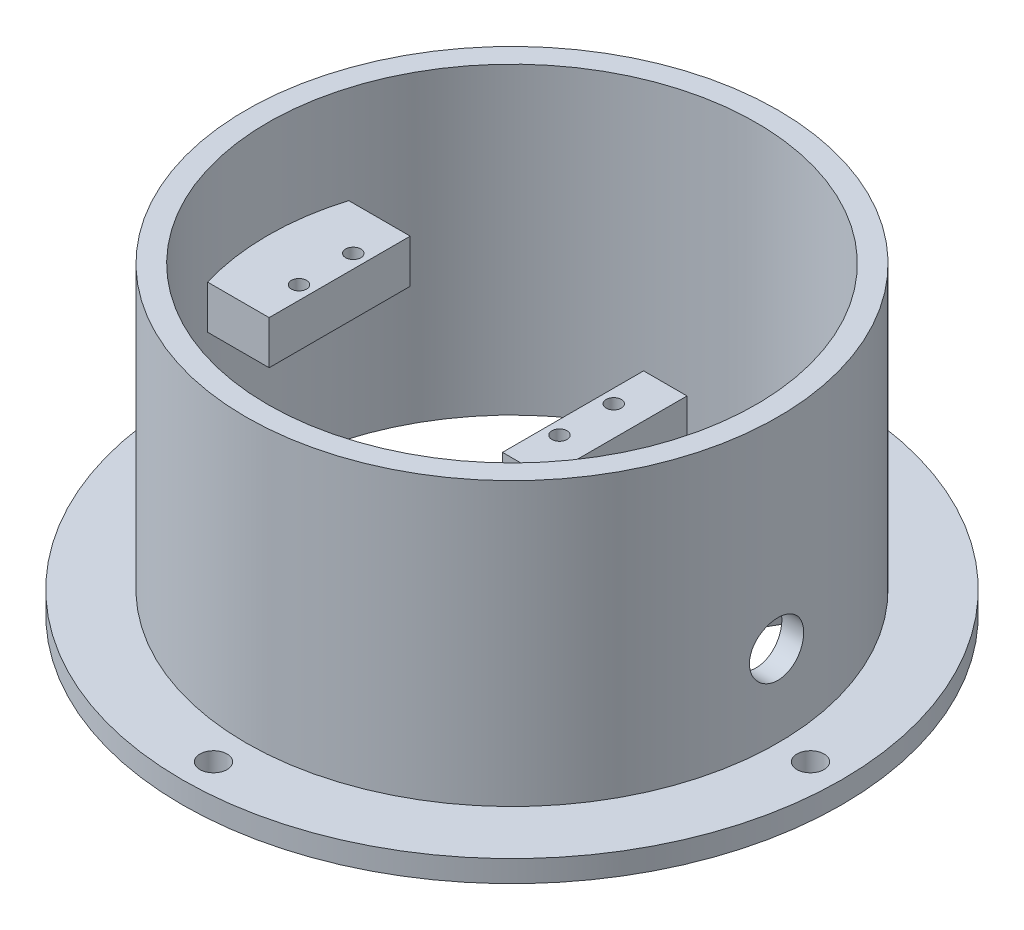
SolidWorks part; units mm, degrees
ref_plane "Front Plane" through (0, 0, 0) normal (0, 0, 1) x (1, 0, 0)
ref_plane "Top Plane" through (0, 0, 0) normal (0, 1, 0) x (1, 0, 0)
ref_plane "Right Plane" through (0, 0, 0) normal (1, 0, 0) x (0, 0, -1)
sketch "Sketch1" plane through (0, 0, 0) normal (0, 1, 0) x (1, 0, 0)
  circle A0 centre (0, 0) radius 45
  circle A1 centre (0, 0) radius 60.75
  dimension "D1" = 90
  dimension "D2" = 121.5
extrude "Boss-Extrude1" add sketch "Sketch1" along normal blind 4
sketch "Sketch2" plane through (0, 4, 0) normal (0, 1, 0) x (1, 0, 0)
  circle A2 centre (0, 0) radius 49
  circle A3 centre (0, 0) radius 49
  circle A5 centre (0, 0) radius 45
  circle A6 centre (0, 0) radius 45
  dimension "D1" = 4
  dimension "D2" = 0
extrude "Boss-Extrude2" add sketch "Sketch2" along normal blind 52
sketch "Sketch3" plane through (0, 0, 0) normal (0, 0, 1) x (1, 0, 0)
  line L0 (0, 0) -> (0, 56) construction
  line L1 (49, 56) -> (-49, 56) construction
  line L2 (-60.75, 0) -> (60.75, 0) construction
  line L3 (11.25, 0) -> (19.25, 0)
  line L4 (11.25, 0) -> (11.25, 38)
  line L5 (11.25, 38) -> (19.25, 38)
  line L6 (19.25, 0) -> (19.25, 38)
  line L7 (45, 56) -> (-45, 56) construction
  line L9 (-46.75, 38) -> (-31.75, 38)
  line L10 (-46.75, 38) -> (-46.75, 30)
  line L11 (-46.75, 30) -> (-31.75, 30)
  line L12 (-31.75, 38) -> (-31.75, 30)
  dimension "D1" = 8
  dimension "D2" = 11.25
  dimension "D3" = 18
  dimension "D4" = 18
  dimension "D5" = 8
  dimension "D6" = 46.75
  dimension "D7" = 15
extrude "Boss-Extrude3" add sketch "Sketch3" along normal mid plane 26
sketch "Sketch4" plane through (11.25, 0, 0) normal (-1, 0, 0) x (0, 0, 1)
  line L0 (0, 0) -> (0, 38) construction
  line L1 (13, 0) -> (-13, 0) construction
  line L2 (13, 38) -> (-13, 38) construction
  line L4 (-5, 5) -> (5, 5)
  line L5 (-5, 5) -> (-5, 28)
  line L6 (-5, 28) -> (5, 28)
  line L7 (5, 5) -> (5, 28)
  line L8 (-5, 5) -> (5, 28) construction
  line L9 (-5, 28) -> (5, 5) construction
  point P6 (0, 16.5)
  dimension "D1" = 5
  dimension "D2" = 10
  dimension "D3" = 10
extrude "Cut-Extrude1" cut sketch "Sketch4" against normal up to surface (8 mm away) up to face at (19.25, 19, 0)
sketch "Sketch5" plane through (11.25, 0, 0) normal (-1, 0, 0) x (0, 0, 1)
  line L0 (0, 28) -> (0, 5) construction
  line L1 (5, 28) -> (-5, 28) construction
  line L2 (-5, 5) -> (5, 5) construction
  circle A0 centre (0, 19) radius 5
  dimension "D1" = 10
  dimension "D2" = 14
extrude "Cut-Extrude2" cut sketch "Sketch5" against normal up to surface (37.75 mm away) contours A0
sketch "Sketch6" plane through (0, 38, 0) normal (0, 1, 0) x (1, 0, 0)
  line L0 (-34.25, 13) -> (-34.25, -13) construction
  line L1 (-31.75, 13) -> (-43.0813, 13) construction
  line L2 (-31.75, -13) -> (-43.0813, -13) construction
  line L3 (-31.75, -13) -> (-31.75, 13) construction
  line L4 (-34.25, 0) -> (13.75, 0) construction
  line L6 (13.75, -13) -> (13.75, 13)
  line L7 (19.25, 13) -> (11.25, 13) construction
  circle A0 centre (-34.25, -5) radius 1.4
  circle A1 centre (13.75, -5) radius 1.4
  circle A2 centre (13.75, 5) radius 1.4
  circle A3 centre (-34.25, 5) radius 1.4
  point P15 (13.75, 0)
  point P19 (0, 0)
  point P24 (0, 0)
  dimension "D3" = 2.8
  dimension "D1" = 2.5
  dimension "D2" = 48
  dimension "D4" = 5
extrude "Cut-Extrude3" cut sketch "Sketch6" against normal blind 7.2 contours A3 | A2 | A1 | A0
sketch "Sketch7" plane through (0, 0, 0) normal (0, -1, 0) x (1, 0, 0)
  line L0 (11.25, 0) -> (45, 0) construction
  line L1 (11.25, 13) -> (11.25, -13) construction
  line L2 (11.25, -13) -> (25.2498, -37.2484)
  line L3 (11.25, 13) -> (11.25, -13)
  line L4 (11.25, 13) -> (25.2498, 37.2484)
  line L5 (24.25, 19.5167) -> (27.3618, 24.9065)
  line L6 (24.25, -19.5167) -> (27.3618, -24.9065)
  line L8 (24.25, 19.5167) -> (24.25, -19.5167)
  line L9 (19.25, 10.8564) -> (27.3618, 24.9065) construction
  line L10 (19.25, 10.8564) -> (19.25, -10.8564) construction
  line L11 (19.25, -10.8564) -> (27.3618, -24.9065) construction
  line L12 (19.25, 13) -> (19.25, -13) construction
  circle A0 centre (0, 0) radius 45 construction
  arc A1 (25.2498, -37.2484) -> (25.2498, 37.2484) centre (0, 0) ccw
  arc A2 (27.3618, -24.9065) -> (27.3618, 24.9065) centre (0, 0) ccw
  dimension "D2" = 8
  dimension "D1" = 60
  dimension "D3" = 5
extrude "Boss-Extrude4" add sketch "Sketch7" against normal blind 4
sketch "Sketch8" plane through (0, 4, 0) normal (0, 1, 0) x (1, 0, 0)
  circle A0 centre (0, 0) radius 55 construction
  circle A1 centre (-55, 0) radius 2.5
  circle A2 centre (0, 55) radius 2.5
  circle A3 centre (55, 0) radius 2.5
  circle A4 centre (0, -55) radius 2.5
  point P6 (0, 0)
  point P7 (-21.9001, -50.4518)
  point P13 (0, 0)
  point P14 (0, 0)
  dimension "D1" = 110
  dimension "D2" = 5
  dimension "D3" = 4
extrude "Cut-Extrude4" cut sketch "Sketch8" against normal blind 4
